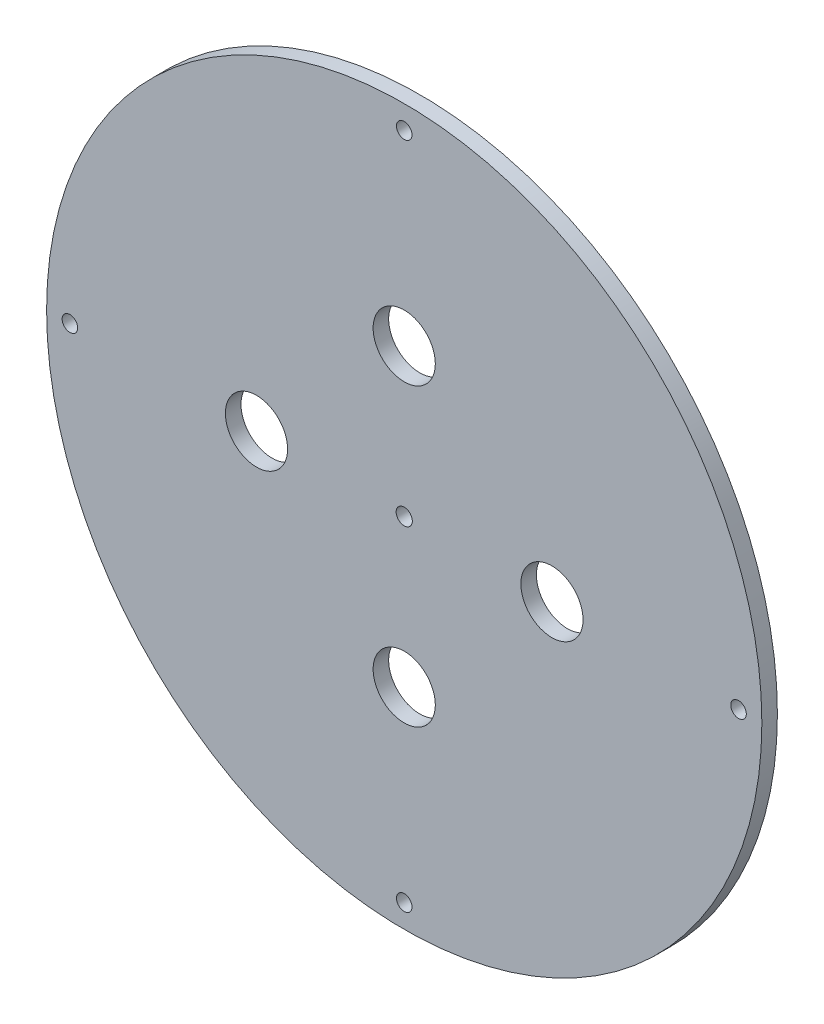
SolidWorks part; units mm, degrees
ref_plane "Front Plane" through (0, 0, 0) normal (0, 0, 1) x (1, 0, 0)
ref_plane "Top Plane" through (0, 0, 0) normal (0, 1, 0) x (1, 0, 0)
ref_plane "Right Plane" through (0, 0, 0) normal (1, 0, 0) x (0, 0, -1)
sketch "Sketch1" plane through (0, 0, 0) normal (0, 0, 1) x (1, 0, 0)
  line L0 (0, 0) -> (0, 79.1155) construction
  circle A0 centre (0, 0) radius 146.05
  circle A1 centre (0, 136.525) radius 3.175
  circle A2 centre (136.525, 0) radius 3.175
  circle A3 centre (0, -136.525) radius 3.175
  circle A4 centre (-136.525, 0) radius 3.175
  circle A9 centre (0, 60.325) radius 12.7
  circle A10 centre (60.325, 0) radius 12.7
  circle A11 centre (0, -60.325) radius 12.7
  circle A12 centre (-60.325, 0) radius 12.7
  circle A13 centre (0, 0) radius 3.302
  point P14 (0, 0)
  point P24 (0, 0)
  dimension "D2" = 6.35
  dimension "D4" = 292.1
  dimension "D6" = 60.325
  dimension "D5" = 25.4
  dimension "D8" = 6.604
  dimension "D3" = 136.525
  dimension "D7" = 4
  dimension "D1" = 4
extrude "Boss-Extrude1" add sketch "Sketch1" along normal blind 6.35
